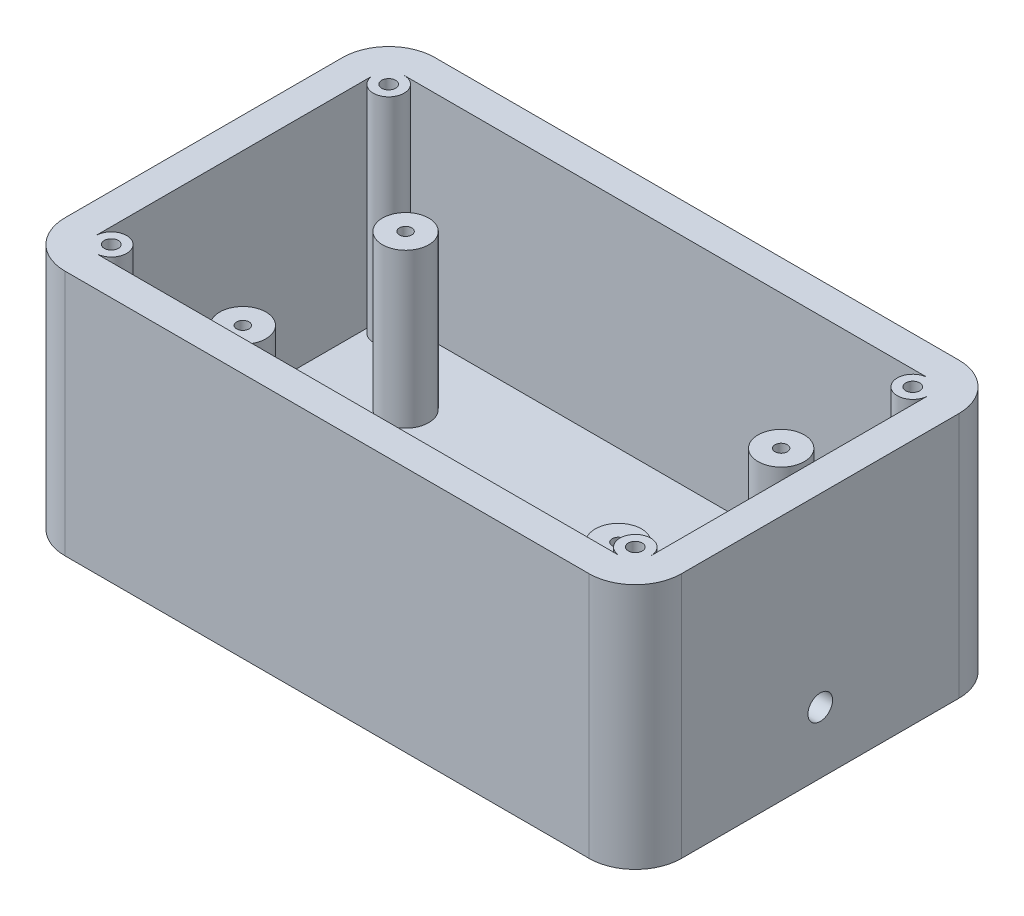
SolidWorks part; units mm, degrees
other "DetailItem1"
other "DetailItem2"
other "DetailItem3"
ref_plane "Front Plane" through (0, 0, 0) normal (0, 0, 1) x (1, 0, 0)
ref_plane "Top Plane" through (0, 0, 0) normal (0, 1, 0) x (1, 0, 0)
ref_plane "Right Plane" through (0, 0, 0) normal (1, 0, 0) x (0, 0, -1)
sketch "Sketch1" plane through (0, 0, 0) normal (0, 1, 0) x (1, 0, 0)
  line L1 (-63.5, -38.1) -> (63.5, -38.1)
  line L2 (-63.5, -38.1) -> (-63.5, 38.1)
  line L3 (-63.5, 38.1) -> (63.5, 38.1)
  line L4 (63.5, -38.1) -> (63.5, 38.1)
  line L5 (-63.5, -38.1) -> (63.5, 38.1) construction
  line L6 (-63.5, 38.1) -> (63.5, -38.1) construction
  point P0 (0, 0)
  dimension "D1" = 76.2
  dimension "D2" = 127
extrude "Boss-Extrude1" add sketch "Sketch1" against normal blind 50.8
fillet "Fillet1" radius 9.525 4 edges at (63.5, -25.4, 38.1) (63.5, -25.4, -38.1) (-63.5, -25.4, -38.1) (-63.5, -25.4, 38.1)
shell "Shell2" thickness 6.35
sketch "Sketch2" plane through (0, -44.45, 0) normal (0, 1, 0) x (1, 0, 0)
  circle A0 centre (-53.975, 28.575) radius 3.175
  arc A1 (-53.975, 31.75) -> (-57.15, 28.575) centre (-53.975, 28.575) ccw construction
extrude "Boss-Extrude2" add sketch "Sketch2" along normal up to surface (44.45 mm away) up to face at (0, 0, 0)
mirror "Mirror1" about plane through (0, 0, 0) normal (1, 0, 0) of "Boss-Extrude2"
mirror "Mirror2" about plane through (0, 0, 0) normal (0, 0, 1) of "Mirror1", "Boss-Extrude2"
hole_wizard "#6-40 Tapped Hole1" positions "3DSketch1" profile "Sketch3" tap size "#6-40" standard "ANSI Inch"
sketch3d "3DSketch1"
  line L0 (-53.975, 0, -28.575) -> (-53.975, -44.45, -28.575) construction
  line L1 (-53.975, 0, 28.575) -> (-53.975, -44.45, 28.575) construction
  line L2 (53.975, 0, 28.575) -> (53.975, -44.45, 28.575) construction
  line L3 (53.975, 0, -28.575) -> (53.975, -44.45, -28.575) construction
  point P0 (-53.975, 0, -28.575)
  point P4 (-53.975, 0, 28.575)
  point P8 (53.975, 0, 28.575)
  point P12 (53.975, 0, -28.575)
cosmetic thread "Hole Thread1" parameters "D1"=7.0104, "D2"=3.5052
cosmetic thread "Hole Thread2" parameters "D1"=7.0104, "D2"=3.5052
cosmetic thread "Hole Thread3" parameters "D1"=7.0104, "D2"=3.5052
cosmetic thread "Hole Thread4" parameters "D1"=7.0104, "D2"=3.5052
sketch "Sketch3" plane through (-53.975, 0, -28.575) normal (1, 0, 0) x (0, 0, 1)
  line L0 (0, 0) -> (0, 13.5623)
  line L1 (0, 13.5623) -> (1.4351, 12.7)
  line L2 (1.4351, 12.7) -> (1.4351, 0)
  line L5 (1.4351, 0) -> (0, 0)
  line L10 (0, 13.5623) -> (-1.4351, 12.7) construction
  line L11 (0, -6.35) -> (0, 107.95) construction
  dimension "Tap Drill Dia." = 2.8702
  dimension "Tap Drill Depth" = 12.7
  dimension "Drill Angle" = 118
sketch "Sketch4" plane through (0, -44.45, 0) normal (0, 1, 0) x (1, 0, 0)
  line L0 (0, -27.94) -> (0, 27.94) construction
  line L5 (-38.6842, 16.764) -> (38.6842, -16.764) construction
  line L6 (-38.6842, -16.764) -> (38.6842, 16.764) construction
  line L7 (-27.94, 0) -> (27.94, 0) construction
  circle A0 centre (-38.6842, 16.764) radius 4.7625
  circle A1 centre (38.6842, 16.764) radius 4.7625
  circle A2 centre (-38.6842, -16.764) radius 4.7625
  circle A3 centre (38.6842, -16.764) radius 4.7625
  point P0 (0, 0)
  dimension "D3" = 9.525
  dimension "D1" = 77.3684
  dimension "D2" = 33.528
extrude "Boss-Extrude3" add sketch "Sketch4" along normal offset from surface (31.75 mm away) 12.7 up to face at (-53.975, 0, -27.1399)
hole_wizard "#6-40 Tapped Hole2" positions "3DSketch2" profile "Sketch5" tap size "#6-40" standard "ANSI Inch"
sketch3d "3DSketch2"
  line L0 (-38.6842, -12.7, -16.764) -> (-38.6842, -44.45, -16.764) construction
  line L1 (38.6842, -12.7, -16.764) -> (38.6842, -44.45, -16.764) construction
  line L2 (-38.6842, -12.7, 16.764) -> (-38.6842, -44.45, 16.764) construction
  circle A0 centre (38.6842, -12.7, 16.764) radius 4.7625 construction
  point P0 (-38.6842, -12.7, -16.764)
  point P4 (38.6842, -12.7, -16.764)
  point P8 (-38.6842, -12.7, 16.764)
  point P12 (38.6842, -12.7, 16.764)
  point P18 (38.6842, -17.4625, 16.764)
sketch "Sketch5" plane through (-38.6842, -12.7, -16.764) normal (1, 0, 0) x (0, 0, 1)
  line L0 (0, 0) -> (0, 9.6785)
  line L1 (0, 9.6785) -> (1.27, 8.9154)
  line L2 (1.27, 8.9154) -> (1.27, 0)
  line L5 (1.27, 0) -> (0, 0)
  line L10 (0, 9.6785) -> (-1.27, 8.9154) construction
  line L11 (0, -6.35) -> (0, 107.95) construction
  dimension "Tap Drill Dia." = 2.54
  dimension "Tap Drill Depth" = 8.9154
  dimension "Drill Angle" = 118
cosmetic thread "Hole Thread5" parameters "D1"=7.0104, "D2"=3.5052
cosmetic thread "Hole Thread6" parameters "D1"=7.0104, "D2"=3.5052
cosmetic thread "Hole Thread7" parameters "D1"=7.0104, "D2"=3.5052
cosmetic thread "Hole Thread8" parameters "D1"=7.0104, "D2"=3.5052
sketch "Sketch7" plane through (-63.5, 0, 0) normal (-1, 0, 0) x (0, 0, 1)
  line L0 (-28.575, -50.8) -> (28.575, -50.8) construction
  circle A0 centre (0, -38.1) radius 2.667
  dimension "D1" = 5.334
  dimension "D2" = 12.7
extrude "Cut-Extrude1" cut sketch "Sketch7" against normal blind 12.7
sketch "Sketch8" plane through (63.5, 0, 0) normal (1, 0, 0) x (0, 0, -1)
  line L2 (-28.575, -50.8) -> (28.575, -50.8) construction
  line L3 (0, 27.94) -> (0, -27.94) construction
  circle A0 centre (0, -38.1) radius 2.54
  point P3 (0, 0)
  dimension "D2" = 5.08
  dimension "D1" = 12.7
extrude "Cut-Extrude2" cut sketch "Sketch8" against normal blind 13.97
hole_wizard "#6-40 Tapped Hole3" positions "3DSketch3" profile "Sketch9" tap size "#6-40" standard "ANSI Inch"
sketch3d "3DSketch3"
  circle A0 centre (-38.6842, -12.7, -16.764) radius 4.7625 construction
  circle A1 centre (-38.6842, -12.7, 16.764) radius 4.7625 construction
  circle A2 centre (38.6842, -12.7, 16.764) radius 4.7625 construction
  circle A3 centre (38.6842, -12.7, -16.764) radius 4.7625 construction
  point P0 (-38.6842, -50.8, -16.764)
  point P2 (-38.6842, -50.8, 16.764)
  point P4 (38.6842, -50.8, 16.764)
  point P6 (38.6842, -50.8, -16.764)
  point P9 (0, 0, 0)
  point P12 (-38.6842, -17.4625, -16.764)
  point P13 (0, 0, 0)
  point P16 (-38.6842, -17.4625, 16.764)
  point P17 (0, 0, 0)
  point P20 (38.6842, -17.4625, 16.764)
  point P21 (0, 0, 0)
  point P24 (38.6842, -17.4625, -16.764)
sketch "Sketch9" plane through (-38.6842, -50.8, -16.764) normal (1, 0, 0) x (0, 0, -1)
  line L0 (0, 0) -> (0, 9.6785)
  line L1 (0, 9.6785) -> (1.27, 8.9154)
  line L2 (1.27, 8.9154) -> (1.27, 0)
  line L5 (1.27, 0) -> (0, 0)
  line L10 (0, 9.6785) -> (-1.27, 8.9154) construction
  line L11 (0, -6.35) -> (0, 107.95) construction
  dimension "Tap Drill Dia." = 2.54
  dimension "Tap Drill Depth" = 8.9154
  dimension "Drill Angle" = 118
cosmetic thread "Hole Thread9" parameters "D1"=7.0104, "D2"=3.5052
cosmetic thread "Hole Thread10" parameters "D1"=7.0104, "D2"=3.5052
cosmetic thread "Hole Thread11" parameters "D1"=7.0104, "D2"=3.5052
cosmetic thread "Hole Thread12" parameters "D1"=7.0104, "D2"=3.5052
